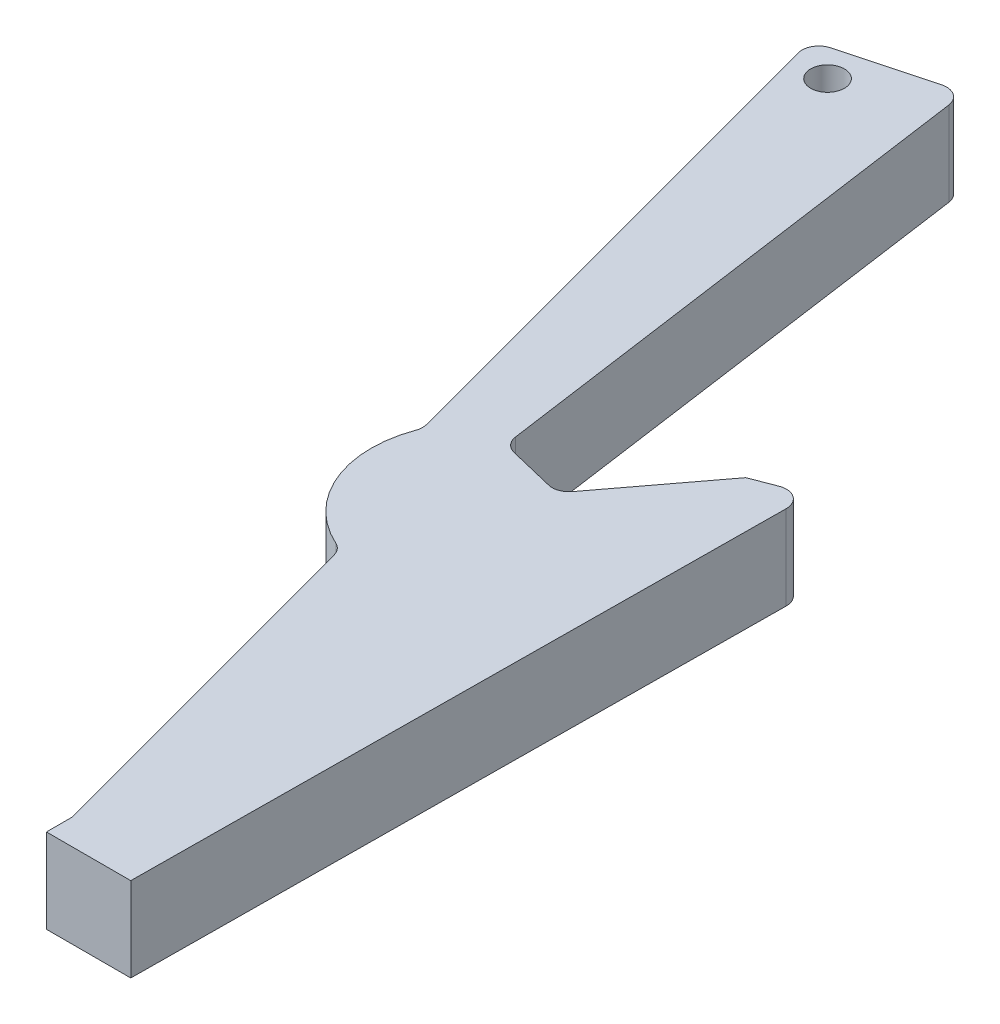
SolidWorks part; units mm, degrees
ref_plane "Front Plane" through (0, 0, 0) normal (0, 0, 1) x (1, 0, 0)
ref_plane "Top Plane" through (0, 0, 0) normal (0, 1, 0) x (1, 0, 0)
ref_plane "Right Plane" through (0, 0, 0) normal (1, 0, 0) x (0, 0, -1)
sketch "Sketch1" plane through (0, 0, 0) normal (0, 1, 0) x (1, 0, 0)
  line L0 (33.784, 86.0591) -> (-60.6847, 86.0591) construction
  line L1 (4.4903, 86.0591) -> (-9.9986, 82.1768)
  line L2 (-9.9986, 82.1768) -> (6.8246, 19.3916)
  line L3 (4.4903, 86.0591) -> (13.3974, 22.6819)
  line L4 (13.3974, 22.6819) -> (21.3974, 20.7504)
  line L5 (21.3974, 20.7504) -> (31.0408, 33.5177)
  line L6 (31.0408, 33.5177) -> (36.6451, 35.6605)
  line L7 (36.6451, 35.6605) -> (35.9561, -44.3395)
  line L8 (35.9561, -44.3395) -> (25.9561, -44.3395)
  line L9 (25.9561, -44.3395) -> (25.9561, -41.3395)
  line L10 (25.9561, -41.3395) -> (14.3092, 2.1272)
  arc A0 (6.8246, 19.3916) -> (14.3092, 2.1272) centre (18.7978, 14.3277) ccw
  dimension "D11" = 13
  dimension "D1" = 15
  dimension "D2" = 15
  dimension "D3" = 90
  dimension "D4" = 65
  dimension "D5" = 83
  dimension "D6" = 64
  dimension "D7" = 8
  dimension "D8" = 16
  dimension "D9" = 6
  dimension "D10" = 80
  dimension "D12" = 45
  dimension "D13" = 3
  dimension "D14" = 10
extrude "Boss-Extrude1" add sketch "Sketch1" along normal blind 10
sketch "Sketch2" plane through (0, 10, 0) normal (0, 1, 0) x (1, 0, 0)
  line L0 (4.4903, 86.0591) -> (-9.9986, 82.1768) construction
  line L1 (-9.9986, 82.1768) -> (6.8246, 19.3916) construction
  circle A0 centre (-5.0996, 79.3484) radius 2
  dimension "D1" = 4
  dimension "D2" = 4
  dimension "D3" = 4
extrude "Cut-Extrude1" cut sketch "Sketch2" against normal through all
fillet "Fillet2" radius 2 7 edges at (14.3092, 5, -2.1272) (6.8246, 5, -19.3916) (13.3974, 5, -22.6819) (21.3974, 5, -20.7504) (36.6451, 5, -35.6605) (4.4903, 5, -86.0591) (-9.9986, 5, -82.1768)
